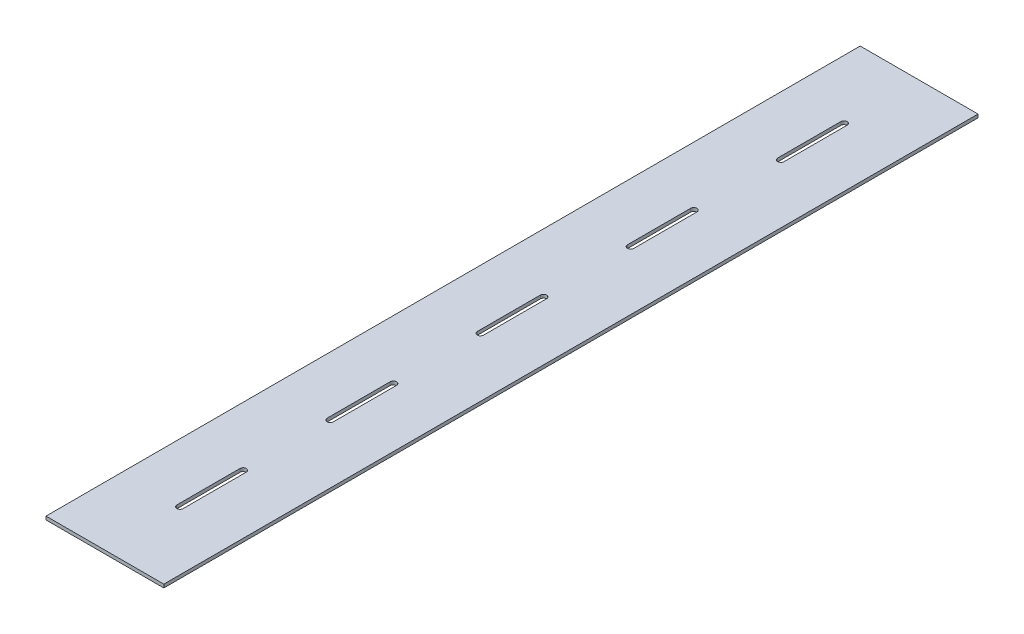
SolidWorks part; units mm, degrees
material "Q355"
ref_plane "前视基准面" through (0, 0, 0) normal (0, 0, 1) x (1, 0, 0)
ref_plane "上视基准面" through (0, 0, 0) normal (0, 1, 0) x (1, 0, 0)
ref_plane "右视基准面" through (0, 0, 0) normal (1, 0, 0) x (0, 0, -1)
sketch "草图1" plane through (0, 0, 0) normal (0, 1, 0) x (1, 0, 0)
  line L1 (-140, 967.5) -> (140, 967.5)
  line L2 (-140, 967.5) -> (-140, -967.5)
  line L3 (-140, -967.5) -> (140, -967.5)
  line L4 (140, 967.5) -> (140, -967.5)
  line L5 (-140, 967.5) -> (140, -967.5) construction
  line L6 (-140, -967.5) -> (140, 967.5) construction
  point P0 (0, 0)
  dimension "D1" = 280
  dimension "D2" = 1935
extrude "凸台-拉伸1" add sketch "草图1" along normal blind 8
sketch "草图2" plane through (0, 8, 0) normal (0, 1, 0) x (1, 0, 0)
  line L0 (140, -967.5) -> (140, 967.5) construction
  line L1 (-140, 967.5) -> (-140, -967.5) construction
  line L3 (0, -789) -> (0, -639) construction
  line L4 (-7.5, -789) -> (-7.5, -639)
  line L5 (7.5, -789) -> (7.5, -639)
  line L6 (-140, -967.5) -> (140, -967.5) construction
  arc A0 (-7.5, -789) -> (7.5, -789) centre (0, -789) ccw
  arc A1 (7.5, -639) -> (-7.5, -639) centre (0, -639) ccw
  point P8 (0, -714)
  dimension "D1" = 7.5
  dimension "D3" = 178.5
  dimension "D2" = 150
extrude "切除-拉伸1" cut sketch "草图2" against normal blind 8
pattern_linear "阵列(线性)1" count 5 spacing 357 along (0, 0, -1) of "切除-拉伸1"
